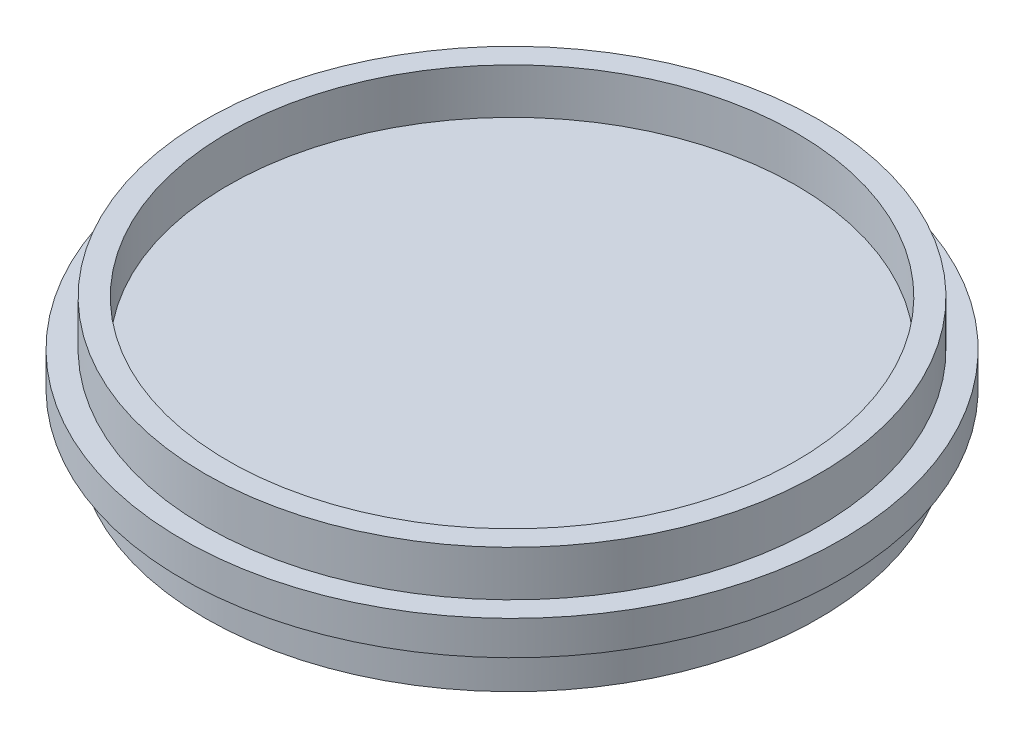
SolidWorks part; units mm, degrees
material "6061-T6 (SS)"
ref_plane "Front Plane" through (0, 0, 0) normal (0, 0, 1) x (1, 0, 0)
ref_plane "Top Plane" through (0, 0, 0) normal (0, 1, 0) x (1, 0, 0)
ref_plane "Right Plane" through (0, 0, 0) normal (1, 0, 0) x (0, 0, -1)
sketch "Sketch1" plane through (0, 0, 0) normal (0, 1, 0) x (1, 0, 0)
  line L5 (0, 0) -> (127.635, 0)
  line L6 (0, 0) -> (0, 127.635)
  line L7 (0, 127.635) -> (127.635, 127.635)
  line L8 (127.635, 0) -> (127.635, 127.635)
  dimension "D1" = 127.635
  dimension "D2" = 127.635
extrude "Boss-Extrude1" add sketch "Sketch1" along normal blind 9.525 contours L5 L8 L7 L6
sketch "Sketch12" plane through (0, 0, 0) normal (0, -1, 0) x (1, 0, 0)
  line L0 (63.8175, 0) -> (63.8175, -127.635) construction
  line L1 (0, 0) -> (127.635, 0) construction
  line L2 (0, -127.635) -> (127.635, -127.635) construction
  line L3 (0, -63.8175) -> (127.635, -63.8175) construction
  line L4 (0, 0) -> (0, -127.635) construction
  line L5 (127.635, 0) -> (127.635, -127.635) construction
  circle A0 centre (63.8175, -63.8175) radius 92.075
  dimension "D1" = 184.15
extrude "Boss-Extrude2" add sketch "Sketch12" against normal up to surface (9.525 mm away) contours A0 up to face at (63.8175, 9.525, -63.8175)
sketch "Sketch5" plane through (0, 9.525, 0) normal (0, 1, 0) x (1, 0, 0)
  circle A0 centre (63.8175, 63.8175) radius 46.355
  circle A3 centre (63.8175, 63.8175) radius 92.075 construction
  dimension "D1" = 92.71
extrude "Cut-Extrude1" [suppressed] cut sketch "Sketch5" against normal blind 9.525
sketch "Sketch11" [suppressed] plane through (0, 9.525, 0) normal (0, 1, 0) x (1, 0, 0)
  line L0 (63.8175, 63.8175) -> (63.8175, 115.443) construction
  circle A0 centre (63.8175, 115.443) radius 1.4351
  dimension "D2" = 2.8702
  dimension "D1" = 51.6255
extrude "Cut-Extrude3" [suppressed] cut sketch "Sketch11" against normal through all contours A0
pattern_circular "CirPattern1" [suppressed] count 12 over 360
sketch "Sketch14" [suppressed] plane through (0, 9.525, 0) normal (0, -1, 0) x (1, 0, 0)
  line L0 (63.8175, -63.8175) -> (147.6375, -63.8175) construction
  line L1 (0, -19.2087) -> (0, 19.2087) construction
  line L2 (147.6375, -63.8175) -> (152.7175, -63.8175)
  line L3 (136.3808, -105.7742) -> (140.8401, -108.2104)
  circle A0 centre (63.8175, -63.8175) radius 46.355 construction
  arc A2 (147.6375, -63.8175) -> (136.3808, -105.7742) centre (63.8175, -63.8175) cw
  arc A3 (152.7175, -63.8175) -> (140.8401, -108.2104) centre (63.8175, -63.8175) cw
  point P0 (63.8175, -63.8175)
  dimension "D1" = 83.82
  dimension "D2" = 88.9
  dimension "D3" = 46.482
  dimension "D4" = 43.942
ref_plane "Support mirror reference plane" through (0, 4.7625, 0) normal (0, 1, 0) x (1, 0, 0)
sketch "Sketch25" [suppressed] plane through (0, 9.525, 0) normal (0, -1, 0) x (1, 0, 0)
  line L0 (63.8175, -63.8175) -> (123.0872, -4.5478) construction
  line L2 (123.0872, -4.5478) -> (126.6793, -0.9557)
  line L3 (144.7953, -42.1754) -> (149.6712, -40.7448)
  line L5 (63.8175, -63.8175) -> (147.6375, -63.8175) construction
  arc A2 (123.0872, -4.5478) -> (144.7953, -42.1754) centre (63.8175, -63.8175) cw
  arc A3 (126.6793, -0.9557) -> (149.6712, -40.7448) centre (63.8175, -63.8175) cw
  point P0 (63.8175, -63.8175)
  dimension "D1" = 83.82
  dimension "D2" = 88.9
  dimension "D3" = 46.482
  dimension "D4" = 43.942
  dimension "D5" = 45
sketch "Sketch30" plane through (0, 0, 0) normal (0, -1, 0) x (1, 0, 0)
  circle A0 centre (63.8175, -63.8175) radius 85.725
  circle A1 centre (63.8175, -63.8175) radius 79.375
  dimension "D1" = 171.45
  dimension "D2" = 158.75
extrude "Boss-Extrude3" add sketch "Sketch30" along normal blind 12.7
mirror "Mirror1" about plane through (0, 4.7625, 0) normal (0, 1, 0) of "Boss-Extrude3"
sketch "Sketch31" plane through (0, 0, 0) normal (0, -1, 0) x (-1, 0, 0)
  line L0 (-63.8175, -52.481) -> (-63.8175, 177.7216) construction
ref_plane "Plane1" through (0, 0, -149.5425) normal (0, 0, -1) x (-1, 0, 0)
ref_plane "Plane2" through (63.8175, 0, 0) normal (-1, 0, 0) x (0, 0, -1)
sketch "Sketch32" plane through (0, 0, -149.5425) normal (0, 0, -1) x (-1, 0, 0)
  line L4 (-63.8175, -87.3125) -> (-63.8175, 87.3125) construction
  line L5 (-149.5425, 0) -> (21.9075, 0) construction
  line L6 (21.9075, 9.525) -> (-149.5425, 9.525) construction
  circle A0 centre (-63.8175, -6.35) radius 1.4351
  circle A1 centre (-63.8175, 15.875) radius 1.4351
  dimension "D1" = 2.8702
  dimension "D2" = 2.8702
  dimension "D3" = 6.35
  dimension "D4" = 6.35
extrude "Cut-Extrude4" [suppressed] cut sketch "Sketch32" against normal blind 15.24
pattern_circular "CirPattern2" [suppressed] count 12 over 360
